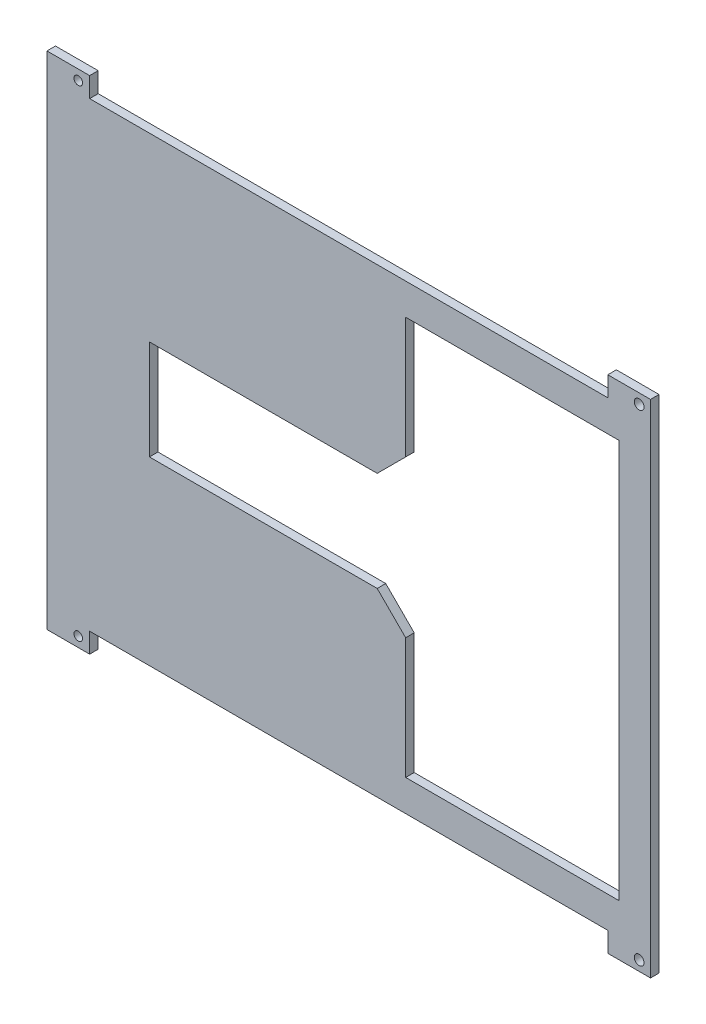
SolidWorks part; units mm, degrees
ref_plane "Front Plane" through (0, 0, 0) normal (0, 0, 1) x (1, 0, 0)
ref_plane "Top Plane" through (0, 0, 0) normal (0, 1, 0) x (1, 0, 0)
ref_plane "Right Plane" through (0, 0, 0) normal (1, 0, 0) x (0, 0, -1)
sketch "Sketch1" plane through (0, 0, 0) normal (0, 0, 1) x (1, 0, 0)
  line L0 (0, 162) -> (212, 162)
  line L2 (0, 0) -> (0, 162)
  line L4 (212, 0) -> (212, 162)
  line L6 (0, 162) -> (0, 169)
  line L7 (0, 169) -> (15, 169)
  line L8 (15, 162) -> (15, 169)
  line L9 (0, 81) -> (212, 81) construction
  line L10 (15, 0) -> (15, -7)
  line L11 (0, -7) -> (15, -7)
  line L12 (0, 0) -> (0, -7)
  line L14 (0, 0) -> (212, 0)
  line L15 (106, 0) -> (106, 162) construction
  line L17 (201, 151) -> (126, 151)
  line L19 (126, 11) -> (201, 11)
  line L21 (126, 98.5) -> (36, 98.5)
  line L22 (36, 98.5) -> (36, 63.5)
  line L23 (36, 63.5) -> (126, 63.5)
  line L24 (126, 151) -> (126, 98.5)
  line L25 (126, 63.5) -> (126, 11)
  line L26 (197, 162) -> (197, 169)
  line L27 (212, 0) -> (197, 0)
  line L28 (212, 0) -> (212, -7)
  line L29 (212, -7) -> (197, -7)
  line L30 (197, 0) -> (197, -7)
  line L31 (212, 169) -> (197, 169)
  line L32 (212, 162) -> (212, 169)
  line L33 (212, 162) -> (197, 162)
  line L35 (201, 151) -> (201, 11)
  circle A0 centre (11, 165.5) radius 1.5
  circle A1 centre (11, -3.5) radius 1.5
  circle A2 centre (208, 165.5) radius 1.7156
  circle A3 centre (208, -3.5) radius 1.7156
  point P22 (206, 81)
  point P27 (119, 64.0108)
  point P28 (119, 81)
  point P43 (197, 81)
  dimension "D5" = 3
  dimension "D6" = 4
  dimension "D11" = 15
  dimension "D13" = 4
  dimension "D15" = 4
  dimension "D16" = 11
  dimension "D1" = 212
  dimension "D2" = 162
  dimension "D3" = 15
  dimension "D4" = 75
  dimension "D7" = 11
  dimension "D8" = 11
  dimension "D9" = 35
  dimension "D10" = 90
  dimension "D12" = 7
  dimension "D14" = 17.5
extrude "Boss-Extrude1" add sketch "Sketch1" along normal blind 3
chamfer "Chamfer1" distance 10 angle 45 2 edges at (126, 63.5, 1.5) (126, 98.5, 1.5)
